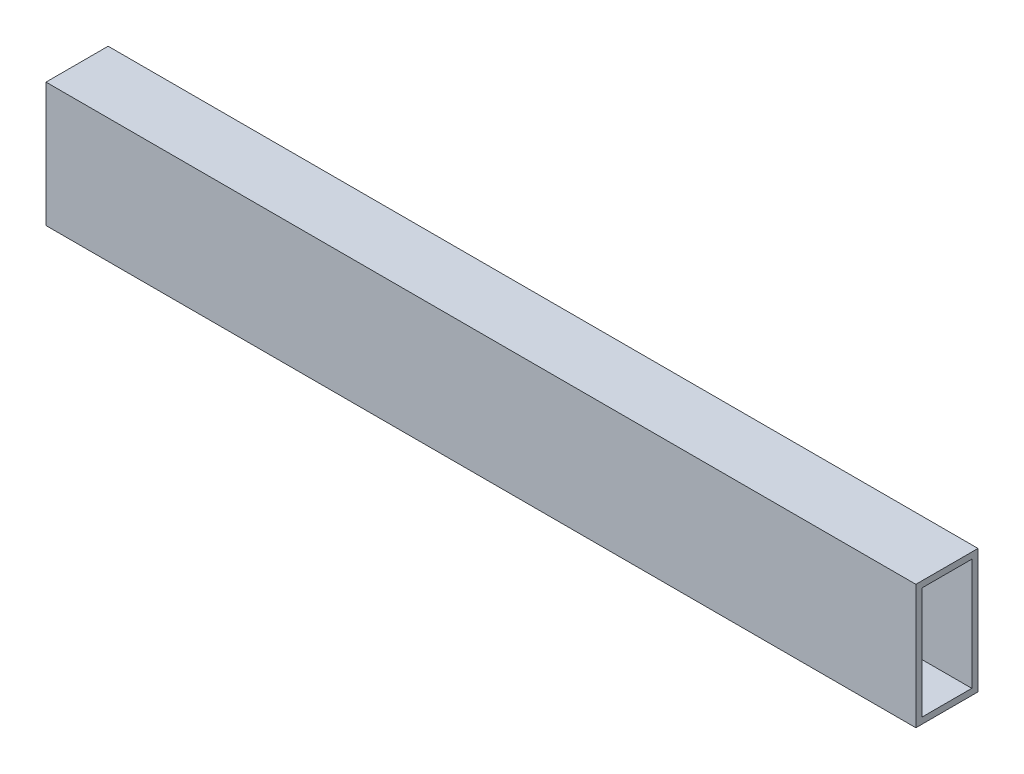
SolidWorks part; units mm, degrees
material "AISI 1015 Steel, Cold Drawn (SS)"
ref_plane "Front Plane" through (0, 0, 0) normal (0, 0, 1) x (1, 0, 0)
ref_plane "Top Plane" through (0, 0, 0) normal (0, 1, 0) x (1, 0, 0)
ref_plane "Right Plane" through (0, 0, 0) normal (1, 0, 0) x (0, 0, -1)
sketch "Sketch1" plane through (0, 0, 0) normal (1, 0, 0) x (0, 0, -1)
  line L0 (45, 5) -> (45, 95)
  line L1 (0, 0) -> (50, 0)
  line L2 (0, 0) -> (0, 100)
  line L3 (0, 100) -> (50, 100)
  line L4 (50, 0) -> (50, 100)
  line L5 (5, 95) -> (45, 95)
  line L6 (5, 5) -> (5, 95)
  line L7 (5, 5) -> (45, 5)
  dimension "D1" = 100
  dimension "D2" = 50
  dimension "D3" = 5
extrude "Boss-Extrude1" add sketch "Sketch1" along normal blind 700
